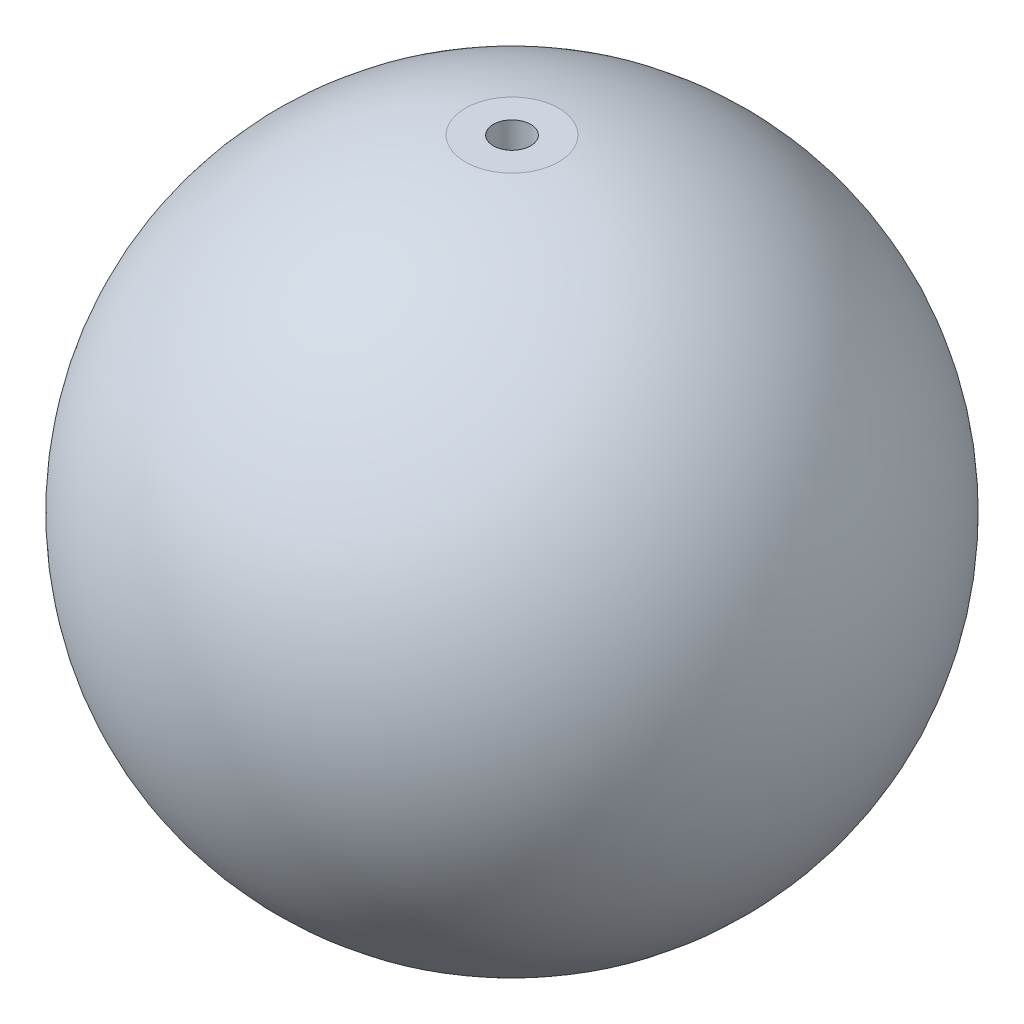
SolidWorks part; units mm, degrees
ref_plane "Plan de face" through (0, 0, 0) normal (0, 0, 1) x (1, 0, 0)
ref_plane "Plan de dessus" through (0, 0, 0) normal (0, 1, 0) x (1, 0, 0)
ref_plane "Plan de droite" through (0, 0, 0) normal (1, 0, 0) x (0, 0, -1)
sketch "Esquisse1" plane through (0, 0, 0) normal (0, 0, 1) x (1, 0, 0)
  line L0 (0, 0) -> (-2, 0) construction
  line L1 (-2, 0) -> (-5, 0)
  line L2 (-2, 0) -> (-2, 70)
  line L3 (-2, 70) -> (-5, 70)
  line L4 (0, 0) -> (0, 50) construction
  line L5 (-5, 3.0333) -> (-5, 3.0333)
  line L6 (-5, 3.0333) -> (-5, 66.9667)
  line L7 (-5, 66.9667) -> (-5, 66.9667)
  arc A0 (-5, 70) -> (-5, 0) centre (0, 35) ccw
  arc A1 (-5, 66.9667) -> (-5, 3.0333) centre (0, 35) ccw
  dimension "D1" = 2
  dimension "D2" = 0
  dimension "D3" = 70
  dimension "D4" = 3
  dimension "D5" = 3
  dimension "D6" = 50
  dimension "D7" = 3
revolve "Révolution1" add sketch "Esquisse1" angle 360 about L4
